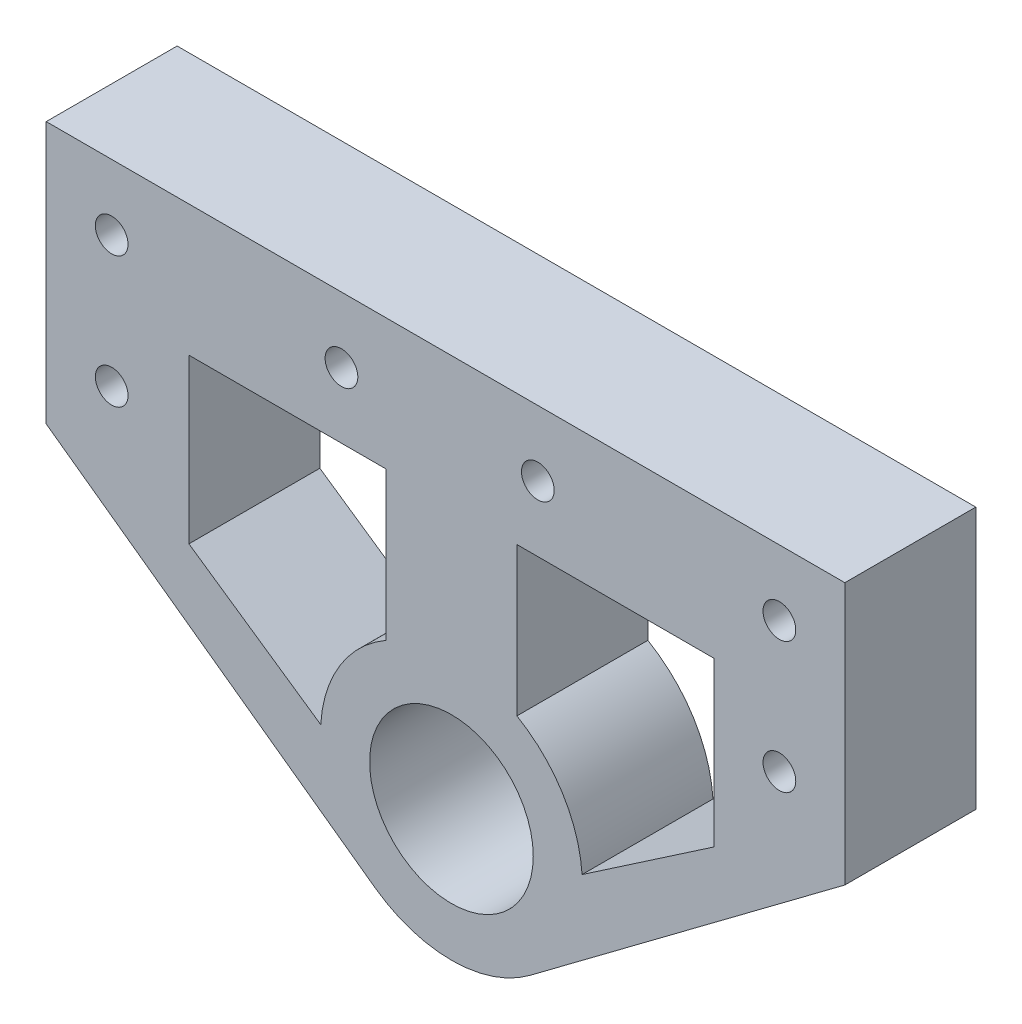
SolidWorks part; units mm, degrees
material "6061 Alloy"
ref_plane "Front Plane" through (0, 0, 0) normal (0, 0, 1) x (1, 0, 0)
ref_plane "Top Plane" through (0, 0, 0) normal (0, 1, 0) x (1, 0, 0)
ref_plane "Right Plane" through (0, 0, 0) normal (1, 0, 0) x (0, 0, -1)
sketch "Sketch1" plane through (0, 0, 0) normal (0, 0, 1) x (1, 0, 0)
  line L4 (41.2458, 19.2768) -> (41.2458, 44.6768)
  line L5 (41.2458, 44.6768) -> (-36.2242, 44.6768)
  line L6 (-36.2242, 44.6768) -> (-36.2242, 19.2768)
  line L8 (-36.2242, 19.2768) -> (3.22, -9.1833)
  line L9 (3.22, -9.1833) -> (41.2458, 19.2768)
  circle A1 centre (3.0823, 6.5768) radius 7.9375
  dimension "D3" = 38.1
  dimension "D4" = 77.47
  dimension "D6" = 15.875
  dimension "D1" = 12.7
  dimension "D2" = 12.7
  dimension "D5" = 25.4
  dimension "D7" = 38.1635
extrude "Boss-Extrude1" add sketch "Sketch1" along normal blind 12.7
sketch "Sketch2" plane through (0, 0, 12.7) normal (0, 0, 1) x (1, 0, 0)
  line L0 (-36.2242, 44.6768) -> (-36.2242, 19.2768) construction
  line L1 (41.2458, 19.2768) -> (41.2458, 44.6768) construction
  line L3 (41.2458, 44.6768) -> (-36.2242, 44.6768) construction
  line L4 (-36.2242, 44.6768) -> (-36.2242, 19.2768) construction
  circle A0 centre (-29.8742, 38.3268) radius 1.5875
  circle A1 centre (-29.8742, 25.6268) radius 1.5875
  circle A2 centre (34.8958, 38.3268) radius 1.5875
  circle A3 centre (34.8958, 25.6268) radius 1.5875
  circle A4 centre (-7.5857, 38.3268) radius 1.5875
  circle A5 centre (11.4643, 38.3268) radius 1.5875
  dimension "D1" = 3.175
  dimension "D2" = 6.35
  dimension "D6" = 3.175
  dimension "D7" = 3.175
  dimension "D3" = 6.35
  dimension "D4" = 6.35
  dimension "D5" = 6.35
  dimension "D8" = 19.05
  dimension "D9" = 28.6385
extrude "Cut-Extrude1" cut sketch "Sketch2" against normal blind 12.7
sketch "Sketch3" plane through (0, 0, 12.7) normal (0, 0, 1) x (1, 0, 0)
  line L0 (-22.3812, 31.9768) -> (-3.2677, 31.9768)
  line L1 (-3.2677, 31.9768) -> (-3.2677, 17.5753)
  line L2 (-22.3812, 31.9768) -> (-22.3812, 16.1255)
  line L3 (-22.3812, 16.1255) -> (-9.5951, 7.3332)
  line L4 (9.4323, 17.5753) -> (9.4323, 31.9768)
  line L5 (9.4323, 31.9768) -> (28.5458, 31.9768)
  line L6 (28.5458, 31.9768) -> (28.5458, 16.1255)
  line L7 (28.5458, 16.1255) -> (15.7549, 7.4113)
  line L8 (41.2458, 44.6768) -> (-36.2242, 44.6768) construction
  line L9 (41.2458, 19.2768) -> (41.2458, 44.6768) construction
  arc A0 (-9.5951, 7.3332) -> (-3.2677, 17.5753) centre (3.0823, 6.5768) cw
  arc A1 (15.7549, 7.4113) -> (9.4323, 17.5753) centre (3.0823, 6.5768) ccw
  dimension "D2" = 12.7
  dimension "D3" = 12.7
  dimension "D1" = 12.7
  dimension "D4" = 12.7
  dimension "D5" = 12.7
extrude "Cut-Extrude2" cut sketch "Sketch3" against normal blind 15.24
fillet "Fillet1" radius 12.7 1 edges at (3.22, -9.1833, 6.35)
